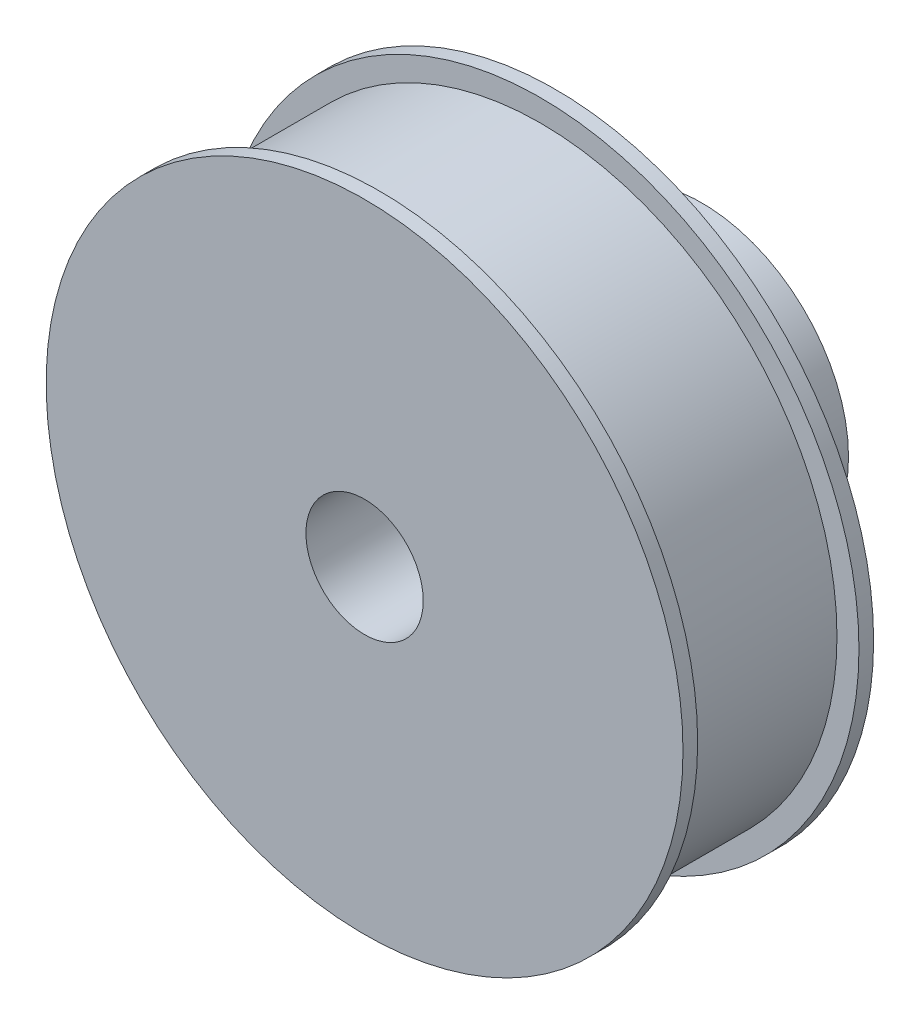
SolidWorks part; units mm, degrees
ref_plane "Front Plane" through (0, 0, 0) normal (0, 0, 1) x (1, 0, 0)
ref_plane "Top Plane" through (0, 0, 0) normal (0, 1, 0) x (1, 0, 0)
ref_plane "Right Plane" through (0, 0, 0) normal (1, 0, 0) x (0, 0, -1)
sketch "Sketch1" plane through (0, 0, 0) normal (0, 1, 0) x (1, 0, 0)
  line L0 (0, 0) -> (0, 161.9291) construction
  line L1 (0, 23) -> (-10, 23)
  line L2 (-10, 23) -> (-10, 13)
  line L3 (-10, 13) -> (-21.7127, 13)
  line L4 (-21.7127, 13) -> (-21.7127, 12)
  line L5 (-21.7127, 12) -> (-20.2127, 12)
  line L6 (-20.2127, 12) -> (-20.2127, 1)
  line L7 (-20.2127, 1) -> (-21.7127, 1)
  line L8 (-21.7127, 1) -> (-21.7127, 0)
  line L9 (-21.7127, 0) -> (0, 0)
  line L10 (0, 0) -> (0, 23)
  line L11 (-21.7127, 12) -> (-21.7127, 1) construction
  dimension "D1" = 20.2127
  dimension "D2" = 1.5
  dimension "D3" = 11
  dimension "D4" = 1
  dimension "D5" = 1
  dimension "D6" = 10
  dimension "D7" = 10
revolve "Revolve1" add sketch "Sketch1" angle 360 about L10
sketch "Sketch2" plane through (0, 0, 0) normal (0, 0, 1) x (1, 0, 0)
  circle A0 centre (0, 0) radius 4
  circle A1 centre (0, 0) radius 21.7127 construction
  dimension "D1" = 8
extrude "Cut-Extrude1" cut sketch "Sketch2" against normal through all
sketch "Sketch3" plane through (0, 0, 0) normal (0, 1, 0) x (1, 0, 0)
  line L0 (0, 23) -> (0, 13) construction
  line L1 (10, 23) -> (-10, 23) construction
  circle A0 centre (0, 18) radius 1.5
  dimension "D1" = 5
  dimension "D2" = 3
extrude "Cut-Extrude2" cut sketch "Sketch3" against normal through all
sketch "Sketch4" plane through (0, 0, 0) normal (1, 0, 0) x (0, 0, -1)
  line L0 (23, 0) -> (13, 0) construction
  line L1 (23, -10) -> (23, 10) construction
  circle A0 centre (18, 0) radius 1.5
  dimension "D1" = 5
  dimension "D2" = 3
extrude "Cut-Extrude3" cut sketch "Sketch4" against normal through all
ref_plane "Plane1" through (0, 0, -6.5) normal (0, 0, 1) x (1, 0, 0)
equation "\"teeth\"= 25"
equation "\"pitch\"= 0.2in"
equation "\"pitch diameter\"= \"teeth\" * \"pitch\" / pi"
equation "\"D1@Sketch1\"=\"pitch diameter\"/2"
